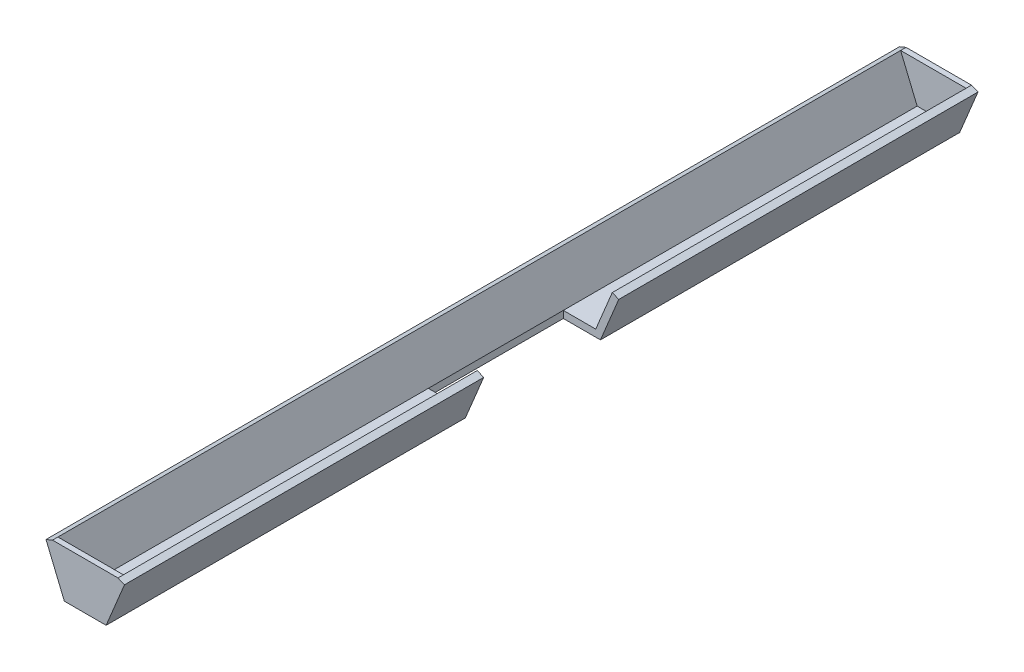
SolidWorks part; units mm, degrees
ref_plane "Plano frontal" through (0, 0, 0) normal (0, 0, 1) x (1, 0, 0)
ref_plane "Plano superior" through (0, 0, 0) normal (0, 1, 0) x (1, 0, 0)
ref_plane "Plano direito" through (0, 0, 0) normal (1, 0, 0) x (0, 0, -1)
sketch "Esboço1" plane through (0, 0, 0) normal (0, 0, 1) x (1, 0, 0)
  line L0 (-3, 0) -> (3, 0)
  line L1 (3, 0) -> (6.0615, 7.391)
  line L2 (-3, 0) -> (-6.0615, 7.391)
  line L3 (0, 0) -> (0, 60.6461) construction
  line L4 (3.8686, -1.3) -> (7.2625, 6.8935)
  line L5 (-3.8686, -1.3) -> (3.8686, -1.3)
  line L6 (-3.8686, -1.3) -> (-7.2625, 6.8935)
  line L7 (6.0615, 7.391) -> (7.2625, 6.8935)
  line L8 (-6.0615, 7.391) -> (-7.2625, 6.8935)
  point P4 (0, 0)
  point P13 (6.9449, 6.9106)
  dimension "D1" = 45
  dimension "D2" = 1.3
  dimension "D3" = 6
  dimension "D4" = 8
extrude "Ressalto-extrusão1" add sketch "Esboço1" along normal mid plane 158
sketch "Esboço2" plane through (0, 0, -79) normal (0, 0, -1) x (-1, 0, 0)
  line L0 (-6.0615, 7.391) -> (6.0615, 7.391)
  line L9 (-3, 0) -> (-6.0615, 7.391)
  line L10 (-6.0615, 7.391) -> (-7.2625, 6.8935)
  line L11 (-7.2625, 6.8935) -> (-3.8686, -1.3)
  line L12 (-3.8686, -1.3) -> (3.8686, -1.3)
  line L13 (3.8686, -1.3) -> (7.2625, 6.8935)
  line L14 (7.2625, 6.8935) -> (6.0615, 7.391)
  line L15 (6.0615, 7.391) -> (3, 0)
  line L16 (3, 0) -> (-3, 0)
  line L18 (-6.0615, 7.391) -> (-7.2625, 6.8935)
  line L19 (-7.2625, 6.8935) -> (-3.8686, -1.3)
  line L20 (-3.8686, -1.3) -> (3.8686, -1.3)
  line L21 (3.8686, -1.3) -> (7.2625, 6.8935)
  line L22 (7.2625, 6.8935) -> (6.0615, 7.391)
  dimension "D1" = 0
extrude "Ressalto-extrusão2" add sketch "Esboço2" against normal blind 1
mirror "Espelhar1" about plane through (0, 0, 0) normal (0, 0, 1) of "Ressalto-extrusão2"
sketch "Esboço4" plane through (0, -1.3, 0) normal (0, -1, 0) x (1, 0, 0)
  line L5 (-3, 12.5) -> (-3, -12.5)
  line L12 (-3, -12.5) -> (20.9721, -12.5)
  line L14 (20.9721, -12.5) -> (20.9721, 12.5)
  line L15 (20.9721, 12.5) -> (-3, 12.5)
  line L16 (-3, 12.5) -> (20.9721, -12.5) construction
  line L18 (-3, 78) -> (-3, -78) construction
  point P2 (3.6682, -10.4861)
  point P4 (8.9861, 0)
  point P9 (0, 0)
  dimension "D1" = 25
extrude "Corte-extrusão1" cut sketch "Esboço4" against normal through all
